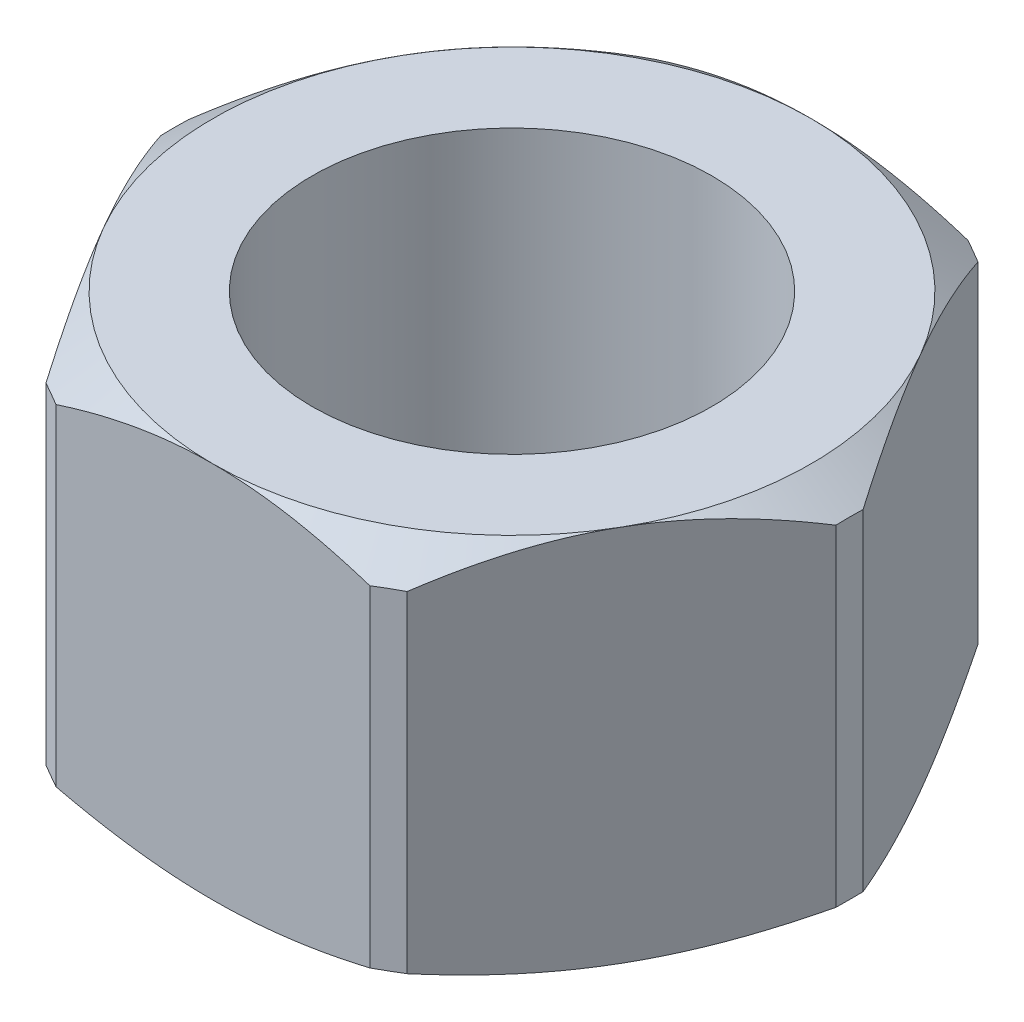
SolidWorks part; units mm, degrees
ref_plane "Alzado" through (0, 0, 0) normal (0, 0, 1) x (1, 0, 0)
ref_plane "Planta" through (0, 0, 0) normal (0, 1, 0) x (1, 0, 0)
ref_plane "Vista lateral" through (0, 0, 0) normal (1, 0, 0) x (0, 0, -1)
sketch "Croquis1" plane through (0, 0, 0) normal (0, 1, 0) x (1, 0, 0)
  line L1 (10.9697, 0) -> (5.4848, 9.5)
  line L2 (5.4848, 9.5) -> (-5.4848, 9.5)
  line L3 (-5.4848, 9.5) -> (-10.9697, 0)
  line L4 (-10.9697, 0) -> (-5.4848, -9.5)
  line L5 (-5.4848, -9.5) -> (5.4848, -9.5)
  line L6 (5.4848, -9.5) -> (10.9697, 0)
  circle A0 centre (0, 0) radius 9.5 construction
  circle A1 centre (0, 0) radius 6.35
  dimension "D2" = 12.7
  dimension "D1" = 19
extrude "Saliente-Extruir1" add sketch "Croquis1" along normal blind 12
sketch "Croquis2" plane through (0, 12, 0) normal (0, 1, 0) x (1, 0, 0)
  circle A0 centre (0, 0) radius 9.5
  circle A1 centre (0, 0) radius 52.8022
extrude "Cortar-Extruir1" cut sketch "Croquis2" against normal blind 12 draft 55
sketch "Croquis3" plane through (0, 0, 0) normal (0, -1, 0) x (1, 0, 0)
  circle A0 centre (0, 0) radius 9.5
  circle A1 centre (0, 0) radius 41.3379
extrude "Cortar-Extruir2" cut sketch "Croquis3" against normal blind 12 draft 63
sketch "Croquis4" plane through (0, 12, 0) normal (0, 1, 0) x (1, 0, 0)
  line L0 (-5.4848, 9.5) -> (0, 0) construction
  line L1 (-5.3598, 9.2835) -> (-6.7234, 8.4963)
  line L2 (-6.7234, 8.4963) -> (-7.3185, 9.5271)
  line L3 (-7.3185, 9.5271) -> (-4.7304, 11.0214)
  line L4 (-4.7304, 11.0214) -> (-4.1352, 9.9905)
  line L5 (-4.1352, 9.9905) -> (-5.3598, 9.2835)
  dimension "D1" = 0.25
extrude "Cortar-Extruir3" cut sketch "Croquis4" against normal up to surface (12 mm away) up to face at (0, 0, 6.35)
pattern_circular "MatrizC1" count 6 every 60 about axis through (0, 12, 0) along (0, 1, 0) of "Cortar-Extruir3"
